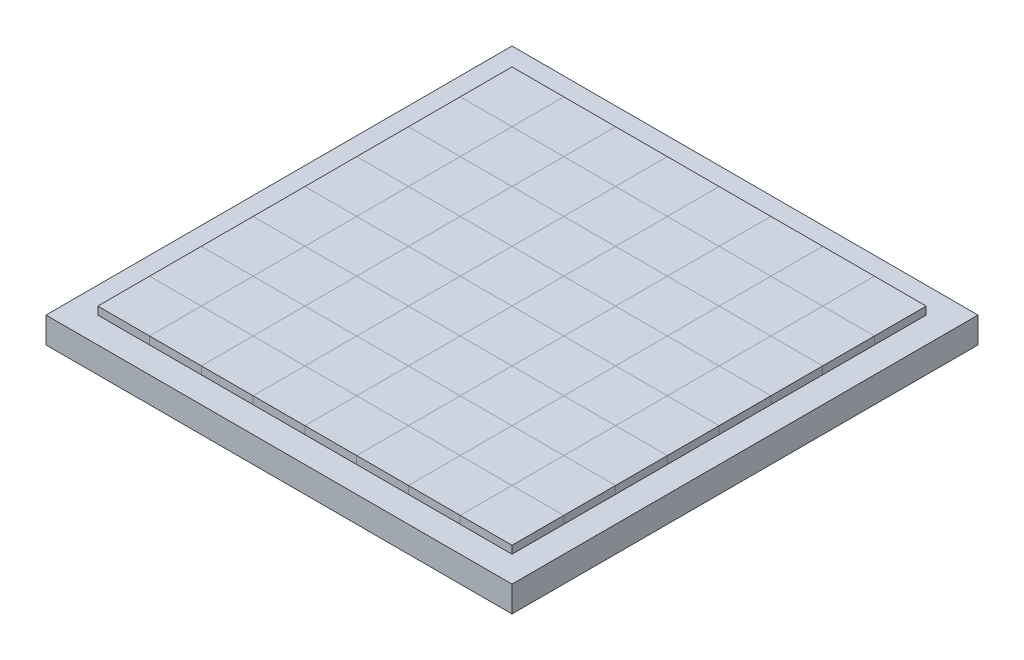
SolidWorks part; units mm, degrees
ref_plane "Front Plane" through (0, 0, 0) normal (0, 0, 1) x (1, 0, 0)
ref_plane "Top Plane" through (0, 0, 0) normal (0, 1, 0) x (1, 0, 0)
ref_plane "Right Plane" through (0, 0, 0) normal (1, 0, 0) x (0, 0, -1)
sketch "Sketch3" plane through (0, 0, 0) normal (0, 1, 0) x (1, 0, 0)
  line L1 (-114.3, 114.3) -> (114.3, 114.3)
  line L2 (-114.3, 114.3) -> (-114.3, -114.3)
  line L3 (-114.3, -114.3) -> (114.3, -114.3)
  line L4 (114.3, 114.3) -> (114.3, -114.3)
  line L5 (-114.3, 114.3) -> (114.3, -114.3) construction
  line L6 (-114.3, -114.3) -> (114.3, 114.3) construction
  point P0 (0, 0)
  dimension "D1" = 228.6
  dimension "D2" = 228.6
extrude "Boss-Extrude3" add sketch "Sketch3" along normal blind 12.7
sketch "Sketch4" plane through (0, 12.7, 0) normal (0, 1, 0) x (1, 0, 0)
  line L0 (114.3, 114.3) -> (-114.3, 114.3) construction
  line L1 (-101.6, 101.6) -> (-76.2, 101.6)
  line L2 (-101.6, 101.6) -> (-101.6, 76.2)
  line L3 (-101.6, 76.2) -> (-76.2, 76.2)
  line L4 (-76.2, 101.6) -> (-76.2, 76.2)
  line L5 (-101.6, 101.6) -> (-76.2, 76.2) construction
  line L6 (-101.6, 76.2) -> (-76.2, 101.6) construction
  line L7 (-114.3, 114.3) -> (-114.3, -114.3) construction
  circle A0 centre (-88.9, 88.9) radius 9.525 construction
  circle A1 centre (-63.5, 88.9) radius 9.525 construction
  circle A2 centre (-38.1, 88.9) radius 9.525 construction
  circle A3 centre (-12.7, 88.9) radius 9.525 construction
  circle A4 centre (12.7, 88.9) radius 9.525 construction
  circle A5 centre (38.1, 88.9) radius 9.525 construction
  circle A6 centre (63.5, 88.9) radius 9.525 construction
  circle A7 centre (88.9, 88.9) radius 9.525 construction
  circle A8 centre (-63.5, 63.5) radius 9.525 construction
  circle A9 centre (-38.1, 63.5) radius 9.525 construction
  circle A10 centre (-12.7, 63.5) radius 9.525 construction
  circle A11 centre (12.7, 63.5) radius 9.525 construction
  circle A12 centre (38.1, 63.5) radius 9.525 construction
  circle A13 centre (63.5, 63.5) radius 9.525 construction
  circle A14 centre (88.9, 63.5) radius 9.525 construction
  circle A15 centre (-63.5, 38.1) radius 9.525 construction
  circle A16 centre (-38.1, 38.1) radius 9.525 construction
  circle A17 centre (-12.7, 38.1) radius 9.525 construction
  circle A18 centre (12.7, 38.1) radius 9.525 construction
  circle A19 centre (38.1, 38.1) radius 9.525 construction
  circle A20 centre (63.5, 38.1) radius 9.525 construction
  circle A21 centre (88.9, 38.1) radius 9.525 construction
  circle A22 centre (-63.5, 12.7) radius 9.525 construction
  circle A23 centre (-38.1, 12.7) radius 9.525 construction
  circle A24 centre (-12.7, 12.7) radius 9.525 construction
  circle A25 centre (12.7, 12.7) radius 9.525 construction
  circle A26 centre (38.1, 12.7) radius 9.525 construction
  circle A27 centre (63.5, 12.7) radius 9.525 construction
  circle A28 centre (88.9, 12.7) radius 9.525 construction
  circle A29 centre (-63.5, -12.7) radius 9.525 construction
  circle A30 centre (-38.1, -12.7) radius 9.525 construction
  circle A31 centre (-12.7, -12.7) radius 9.525 construction
  circle A32 centre (12.7, -12.7) radius 9.525 construction
  circle A33 centre (38.1, -12.7) radius 9.525 construction
  circle A34 centre (63.5, -12.7) radius 9.525 construction
  circle A35 centre (88.9, -12.7) radius 9.525 construction
  circle A36 centre (-63.5, -38.1) radius 9.525 construction
  circle A37 centre (-38.1, -38.1) radius 9.525 construction
  circle A38 centre (-12.7, -38.1) radius 9.525 construction
  circle A39 centre (12.7, -38.1) radius 9.525 construction
  circle A40 centre (38.1, -38.1) radius 9.525 construction
  circle A41 centre (63.5, -38.1) radius 9.525 construction
  circle A42 centre (88.9, -38.1) radius 9.525 construction
  circle A43 centre (-63.5, -63.5) radius 9.525 construction
  circle A44 centre (-38.1, -63.5) radius 9.525 construction
  circle A45 centre (-12.7, -63.5) radius 9.525 construction
  circle A46 centre (12.7, -63.5) radius 9.525 construction
  circle A47 centre (38.1, -63.5) radius 9.525 construction
  circle A48 centre (63.5, -63.5) radius 9.525 construction
  circle A49 centre (88.9, -63.5) radius 9.525 construction
  circle A50 centre (-63.5, -88.9) radius 9.525 construction
  circle A51 centre (-38.1, -88.9) radius 9.525 construction
  circle A52 centre (-12.7, -88.9) radius 9.525 construction
  circle A53 centre (12.7, -88.9) radius 9.525 construction
  circle A54 centre (38.1, -88.9) radius 9.525 construction
  circle A55 centre (63.5, -88.9) radius 9.525 construction
  circle A56 centre (88.9, -88.9) radius 9.525 construction
  circle A57 centre (-88.9, 63.5) radius 9.525 construction
  circle A58 centre (-88.9, 38.1) radius 9.525 construction
  circle A59 centre (-88.9, 12.7) radius 9.525 construction
  circle A60 centre (-88.9, -12.7) radius 9.525 construction
  circle A61 centre (-88.9, -38.1) radius 9.525 construction
  circle A62 centre (-88.9, -63.5) radius 9.525 construction
  circle A63 centre (-88.9, -88.9) radius 9.525 construction
  point P0 (-88.9, 88.9)
  dimension "D5" = 19.05
  dimension "D6" = 8
  dimension "D1" = 25.4
  dimension "D2" = 25.4
  dimension "D3" = 12.7
  dimension "D4" = 12.7
  dimension "D7" = 8
extrude "Boss-Extrude4" add sketch "Sketch4" along normal blind 3.81
pattern_linear "LPattern1" count 4 spacing 50.8 along (1, 0, 0) count 4 spacing 50.8 along (0, 0, 1) of "Boss-Extrude4"
sketch "Sketch5" plane through (0, 12.7, 0) normal (0, 1, 0) x (1, 0, 0)
  line L1 (-76.2, 101.6) -> (-50.8, 101.6)
  line L2 (-76.2, 101.6) -> (-76.2, 76.2)
  line L3 (-76.2, 76.2) -> (-50.8, 76.2)
  line L4 (-50.8, 101.6) -> (-50.8, 76.2)
extrude "Boss-Extrude6" add sketch "Sketch5" along normal blind 3.81 separate body contours L2 L1 L4 L3
pattern_linear "LPattern2" count 4 spacing 50.8 along (1, 0, 0) count 4 spacing 50.8 along (0, 0, 1) of "Boss-Extrude6"
sketch "Sketch6" plane through (0, 12.7, 0) normal (0, 1, 0) x (1, 0, 0)
  line L1 (-101.6, 76.2) -> (-76.2, 76.2)
  line L2 (-101.6, 76.2) -> (-101.6, 50.8)
  line L3 (-101.6, 50.8) -> (-76.2, 50.8)
  line L4 (-76.2, 76.2) -> (-76.2, 50.8)
extrude "Boss-Extrude7" add sketch "Sketch6" along normal blind 3.81 separate body
pattern_linear "LPattern3" count 4 spacing 50.8 along (1, 0, 0) count 4 spacing 50.8 along (0, 0, 1) of "Boss-Extrude7"
sketch "Sketch7" plane through (0, 12.7, 0) normal (0, 1, 0) x (1, 0, 0)
  line L1 (-76.2, 50.8) -> (-50.8, 50.8)
  line L2 (-76.2, 50.8) -> (-76.2, 76.2)
  line L3 (-76.2, 76.2) -> (-50.8, 76.2)
  line L4 (-50.8, 50.8) -> (-50.8, 76.2)
extrude "Boss-Extrude8" add sketch "Sketch7" along normal blind 3.81 separate body
pattern_linear "LPattern4" count 4 spacing 50.8 along (1, 0, 0) count 4 spacing 50.8 along (0, 0, 1) of "Boss-Extrude8"
